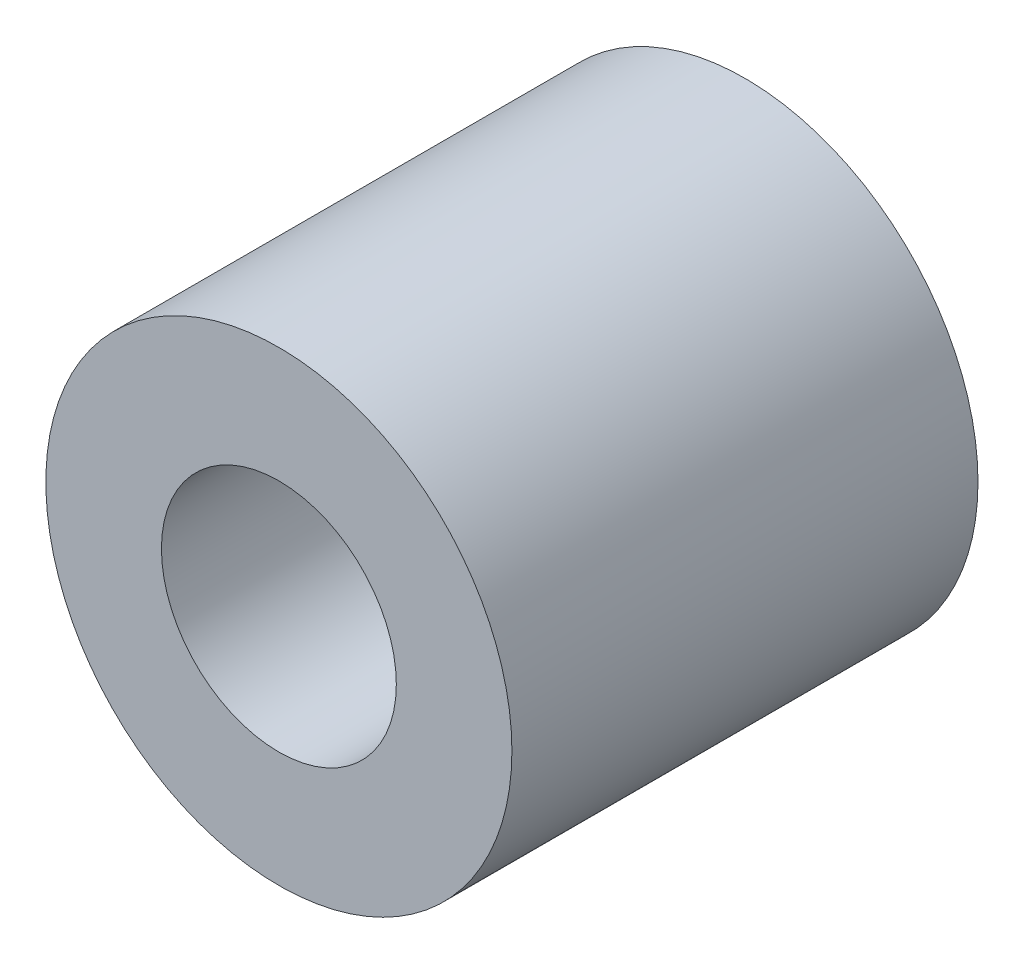
SolidWorks part; units mm, degrees
ref_plane "Front Plane" through (0, 0, 0) normal (0, 0, 1) x (1, 0, 0)
ref_plane "Top Plane" through (0, 0, 0) normal (0, 1, 0) x (1, 0, 0)
ref_plane "Right Plane" through (0, 0, 0) normal (1, 0, 0) x (0, 0, -1)
sketch "Sketch1" plane through (0, 0, 0) normal (0, 0, 1) x (1, 0, 0)
  circle A0 centre (0, 0) radius 6.35
  circle A1 centre (0, 0) radius 3.2004
  dimension "OD" = 12.7
  dimension "ID" = 6.4008
extrude "Extrude1" add sketch "Sketch1" along normal mid plane 12.7
sketch "Sketch2" plane through (0, 0, 0) normal (1, 0, 0) x (0, 0, -1)
  line L0 (-6.35, -3.2004) -> (6.35, -3.2004) construction
  line L3 (6.35, 3.2004) -> (-6.35, 3.2004) construction
  line L5 (-6.35, -3.2004) -> (6.35, -3.2004)
  line L6 (6.35, 3.2004) -> (-6.35, 3.2004)
sketch "Sketch4" plane through (0, 0, 6.35) normal (0, 0, 1) x (1, 0, 0)
  line L0 (0, 0) -> (-2.263, 2.263)
  line L1 (0, -3.4925) -> (0, 3.4925) construction
  circle A0 centre (0, 0) radius 3.2004 construction
  dimension "D1" = 45
